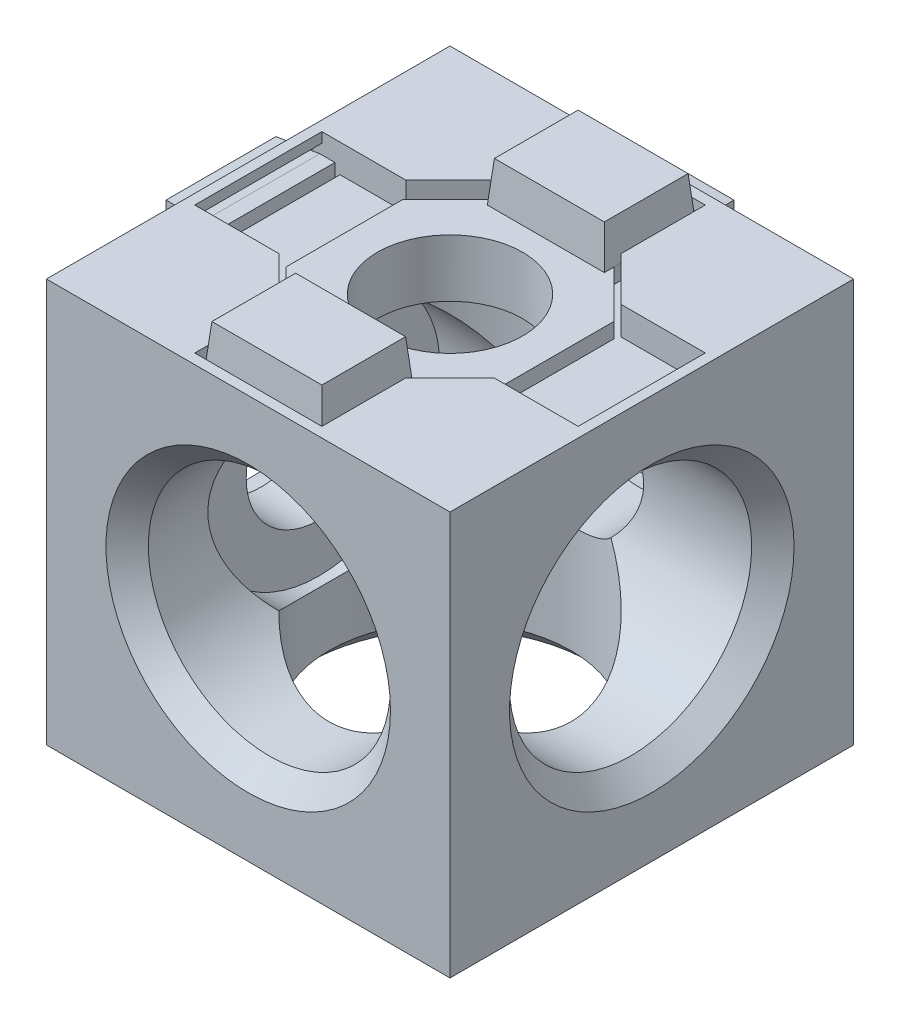
SolidWorks part; units mm, degrees
ref_plane "Front Plane" through (0, 0, 0) normal (0, 0, 1) x (1, 0, 0)
ref_plane "Top Plane" through (0, 0, 0) normal (0, 1, 0) x (1, 0, 0)
ref_plane "Right Plane" through (0, 0, 0) normal (1, 0, 0) x (0, 0, -1)
sketch "Sketch1" plane through (0, 0, 0) normal (0, 0, 1) x (1, 0, 0)
  line L0 (-10, -10) -> (10, 10) construction
  line L1 (-10, 10) -> (10, 10)
  line L2 (-10, 10) -> (-10, -10)
  line L3 (-10, -10) -> (10, -10)
  line L4 (10, 10) -> (10, -10)
  dimension "D1" = 20
extrude "Extrude1" add sketch "Sketch1" along normal mid plane 20
sketch "Sketch2" plane through (0, 0, 10) normal (0, 0, 1) x (1, 0, 0)
  circle A0 centre (0, 0) radius 6
  dimension "D1" = 12
extrude "Cut-Extrude1" cut sketch "Sketch2" against normal through all
sketch "Sketch3" plane through (0, 0, 10) normal (0, 0, 1) x (1, 0, 0)
  circle A0 centre (0, 0) radius 7.05
  dimension "D1" = 14.1
extrude "Cut-Extrude2" cut sketch "Sketch3" against normal through all draft 45
sketch "Sketch4" plane through (0, 0, -10) normal (0, 0, -1) x (-1, 0, 0)
  circle A0 centre (0, 0) radius 3.6
  circle A1 centre (0, 0) radius 6 construction
  circle A2 centre (0, 0) radius 6
  dimension "D1" = 7.2
extrude "Extrude2" add sketch "Sketch4" against normal blind 6
sketch "Sketch14" plane through (0, 0, -10) normal (0, 0, -1) x (-1, 0, 0)
  line L0 (-3.15, 5.3353) -> (-5.3353, 3.15)
  line L1 (-3.15, 9.5) -> (3.15, 9.5)
  line L2 (-3.15, 9.5) -> (-3.15, 5.3353)
  line L3 (-3.15, -9.5) -> (3.15, -9.5)
  line L4 (3.15, 9.5) -> (3.15, 5.3353)
  line L5 (-9.5, 3.15) -> (-5.3353, 3.15)
  line L6 (-9.5, 3.15) -> (-9.5, -3.15)
  line L7 (-9.5, -3.15) -> (-5.3353, -3.15)
  line L8 (9.5, 3.15) -> (9.5, -3.15)
  line L9 (3.15, 5.3353) -> (5.3353, 3.15)
  line L10 (-5.3353, -3.15) -> (-3.15, -5.3353)
  line L11 (5.3353, -3.15) -> (3.15, -5.3353)
  line L12 (-3.15, -5.3353) -> (-3.15, -9.5)
  line L13 (0, 0) -> (-9.5, 0) construction
  line L14 (3.15, -5.3353) -> (3.15, -9.5)
  line L15 (5.3353, -3.15) -> (9.5, -3.15)
  line L16 (5.3353, 3.15) -> (9.5, 3.15)
  line L17 (0, 0) -> (0, 9.5) construction
  dimension "D1" = 6.3
  dimension "D2" = 12
  dimension "D4" = 19
extrude "Cut-Extrude7" cut sketch "Sketch14" against normal blind 1.4
sketch "Sketch15" plane through (0, 0, -8.6) normal (0, 0, -1) x (-1, 0, 0)
  line L16 (-5.2317, 2.9) -> (-5.2317, -2.9)
  line L17 (5.2317, -2.9) -> (5.2317, 2.9)
  line L32 (-2.9, 9.25) -> (-2.9, 5.2317)
  line L33 (-2.9, 5.2317) -> (-5.2317, 2.9)
  line L34 (-5.2317, 2.9) -> (-9.25, 2.9)
  line L35 (-9.25, 2.9) -> (-9.25, -2.9)
  line L36 (-9.25, -2.9) -> (-5.2317, -2.9)
  line L37 (-5.2317, -2.9) -> (-2.9, -5.2317)
  line L38 (-2.9, -5.2317) -> (-2.9, -9.25)
  line L39 (-2.9, -9.25) -> (2.9, -9.25)
  line L40 (2.9, -9.25) -> (2.9, -5.2317)
  line L41 (2.9, -5.2317) -> (5.2317, -2.9)
  line L42 (5.2317, -2.9) -> (9.25, -2.9)
  line L43 (9.25, -2.9) -> (9.25, 2.9)
  line L44 (9.25, 2.9) -> (5.2317, 2.9)
  line L45 (5.2317, 2.9) -> (2.9, 5.2317)
  line L46 (2.9, 5.2317) -> (2.9, 9.25)
  line L47 (2.9, 9.25) -> (-2.9, 9.25)
  line L48 (-2.9, 9.25) -> (-2.9, 5.2317)
  line L49 (-2.9, 5.2317) -> (-5.2317, 2.9)
  line L53 (-5.2317, -2.9) -> (-2.9, -5.2317)
  line L54 (-2.9, -5.2317) -> (-2.9, -9.25)
  line L55 (-2.9, -9.25) -> (2.9, -9.25)
  line L56 (2.9, -9.25) -> (2.9, -5.2317)
  line L57 (2.9, -5.2317) -> (5.2317, -2.9)
  line L61 (5.2317, 2.9) -> (2.9, 5.2317)
  line L62 (2.9, 5.2317) -> (2.9, 9.25)
  line L63 (2.9, 9.25) -> (-2.9, 9.25)
  circle A0 centre (0, 0) radius 3.6 construction
  circle A1 centre (0, 0) radius 3.6
  dimension "D1" = 0.25
extrude "Extrude4" add sketch "Sketch15" along normal blind 0.75
sketch "Sketch16" plane through (0, 0, -9.35) normal (0, 0, -1) x (-1, 0, 0)
  line L0 (2.9, 5.2317) -> (2.9, 9.25) construction
  line L1 (-2.9, 9.25) -> (2.9, 9.25)
  line L2 (-2.9, 9.25) -> (-2.9, 4.75)
  line L3 (-2.9, 4.75) -> (2.9, 4.75)
  line L4 (2.9, 9.25) -> (2.9, 4.75)
  line L5 (-2.9, -9.25) -> (2.9, -9.25)
  line L6 (-2.9, -9.25) -> (-2.9, -4.75)
  line L7 (-2.9, -4.75) -> (2.9, -4.75)
  line L8 (2.9, -9.25) -> (2.9, -4.75)
  dimension "D1" = 4.5
extrude "Extrude5" add sketch "Sketch16" along normal blind 2 draft 5
sketch "Sketch7" plane through (0, 0, 0) normal (0, 1, 0) x (1, 0, 0)
  line L0 (0, 0) -> (-10, 0) construction
  line L1 (-10, -10) -> (-10, 10) construction
ref_axis "Axis1" through (-10, 0, 0) along (1, 0, 0)
sketch "Sketch9" plane through (0, 0, 0) normal (0, 0, 1) x (1, 0, 0)
  line L0 (0, 0) -> (0, 11.5939) construction
ref_axis "Axis2" through (0, 11.5939, 0) along (0, -1, 0)
sketch "Sketch13" plane through (0, 0, 0) normal (1, 0, 0) x (0, 0, -1)
  line L0 (-10, -7.5) -> (-10, -6)
  line L1 (-10, -6) -> (-7, -6)
  line L2 (-7, -6) -> (-7, -5.5)
  line L3 (-7, -5.5) -> (-10, -5.5)
  line L4 (-10, -5.5) -> (-10, 0)
  line L5 (-10, 0) -> (-11.5, 0)
  line L6 (-10, -7.5) -> (-10.5, -7.5)
  line L7 (-10, -10) -> (-10, 10) construction
  line L8 (0, 0) -> (-10, 0) construction
  arc A0 (-10.5, -7.5) -> (-11.5, 0) centre (17.125, 0) cw
  dimension "D1" = 1.5
  dimension "D2" = 0.5
  dimension "D3" = 3
  dimension "D4" = 1.5
pattern_circular "CirPattern1" count 2 over 90 about axis through (0, 0, 0) along (1, 0, 0) of "Cut-Extrude1", "Extrude2", "Cut-Extrude7", "Extrude4", "Extrude5", "Cut-Extrude2"
pattern_circular "CirPattern2" count 2 over 90 about axis through (0, 0, 0) along (0, 1, 0) of "Cut-Extrude1", "Extrude2", "Extrude5", "Extrude4", "Cut-Extrude7", "Cut-Extrude2"
sketch "Sketch23" plane through (-4, 0, 0) normal (1, 0, 0) x (0, 0, -1)
  circle A0 centre (0, 0) radius 6
extrude "Cut-Extrude15" cut sketch "Sketch23" against normal blind 2.5
sketch "Sketch24" plane through (0, 4, 0) normal (0, -1, 0) x (1, 0, 0)
  circle A0 centre (0, 0) radius 6
extrude "Cut-Extrude16" cut sketch "Sketch24" against normal blind 2.5
